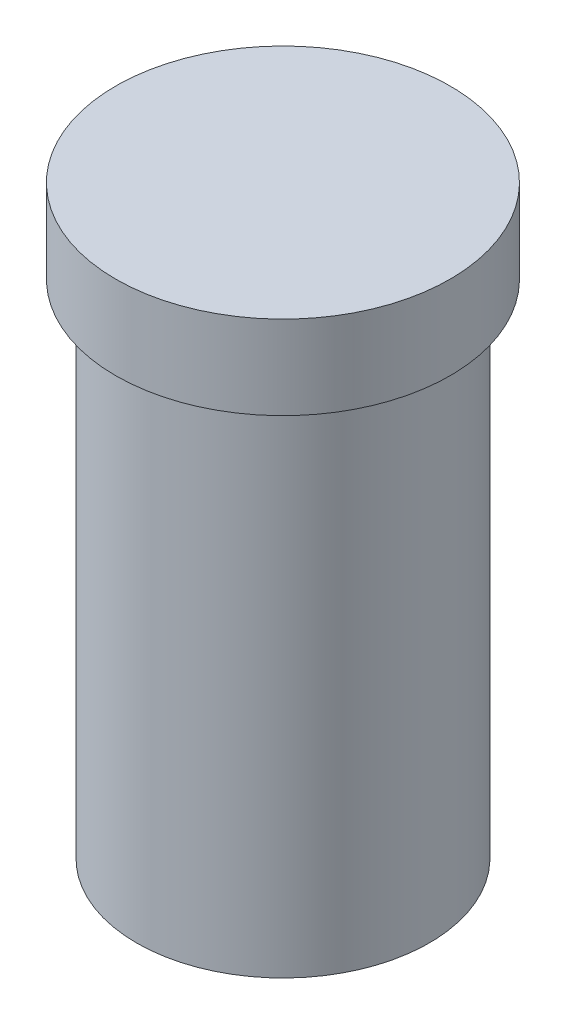
SolidWorks part; units mm, degrees
ref_plane "Plan de face" through (0, 0, 0) normal (0, 0, 1) x (1, 0, 0)
ref_plane "Plan de dessus" through (0, 0, 0) normal (0, 1, 0) x (1, 0, 0)
ref_plane "Plan de droite" through (0, 0, 0) normal (1, 0, 0) x (0, 0, -1)
sketch "Esquisse1" plane through (0, 0, 0) normal (0, 1, 0) x (1, 0, 0)
  circle A0 centre (0, 0) radius 4
  circle A1 centre (0, 0) radius 1.75
extrude "Boss.-Extru.1" add sketch "Esquisse1" against normal blind 6 contours A1
sketch "Esquisse2" plane through (0, 0, 0) normal (0, 1, 0) x (1, 0, 0)
  circle A0 centre (0, 0) radius 2
extrude "Boss.-Extru.2" add sketch "Esquisse2" along normal blind 1
